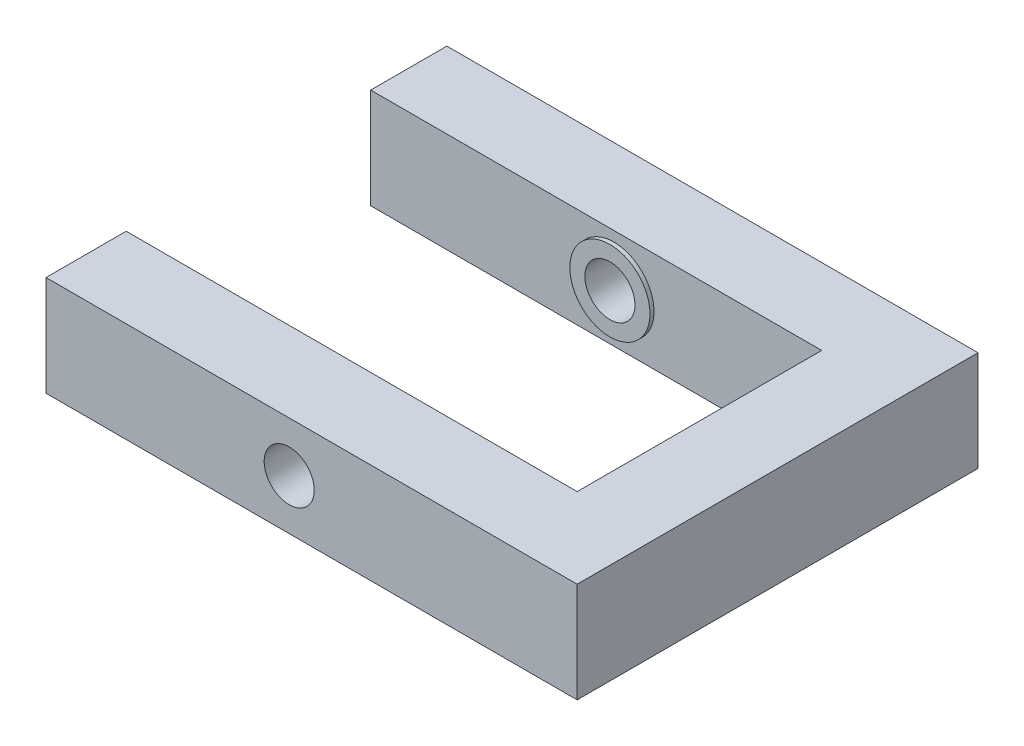
SolidWorks part; units mm, degrees
ref_plane "Front Plane" through (0, 0, 0) normal (0, 0, 1) x (1, 0, 0)
ref_plane "Top Plane" through (0, 0, 0) normal (0, 1, 0) x (1, 0, 0)
ref_plane "Right Plane" through (0, 0, 0) normal (1, 0, 0) x (0, 0, -1)
sketch "Sketch1" plane through (0, 0, 0) normal (0, 1, 0) x (1, 0, 0)
  line L0 (0, -12) -> (0, -20)
  line L3 (0, -12) -> (45, -12)
  line L4 (45, 12) -> (45, -12)
  line L5 (0, 20) -> (53, 20)
  line L6 (0, 20) -> (0, 12.4)
  line L7 (0, -20) -> (53, -20)
  line L8 (53, 20) -> (53, -20)
  line L12 (0, 12.4) -> (45, 12.4)
  line L13 (45, 12) -> (45, 12.4)
  point P8 (45, 0)
  point P10 (53, 0)
  dimension "D1" = 24
  dimension "D4" = 8
  dimension "D5" = 0.4
extrude "Boss-Extrude1" add sketch "Sketch1" along normal blind 10
sketch "Sketch2" plane through (0, 0, 20) normal (0, 0, 1) x (1, 0, 0)
  line L0 (0, 10) -> (0, 0) construction
  line L1 (53, 10) -> (53, 0) construction
  circle A0 centre (24.27, 5) radius 2.5
  point P4 (0, 0)
  dimension "D2" = 5
  dimension "D1" = 24.27
extrude "Cut-Extrude1" cut sketch "Sketch2" against normal blind 59
sketch "Sketch3" plane through (0, 0, -12.4) normal (0, 0, 1) x (1, 0, 0)
  circle A0 centre (24.27, 5) radius 4
  circle A1 centre (24.27, 5) radius 2.5
  dimension "D1" = 8
extrude "Boss-Extrude2" add sketch "Sketch3" along normal blind 0.4
